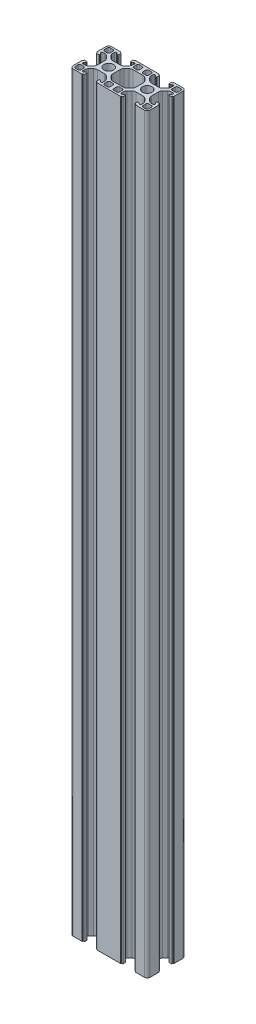
SolidWorks part; units mm, degrees
ref_plane "Спереди" through (0, 0, 0) normal (0, 0, 1) x (1, 0, 0)
ref_plane "Сверху" through (0, 0, 0) normal (0, 1, 0) x (1, 0, 0)
ref_plane "Справа" through (0, 0, 0) normal (1, 0, 0) x (0, 0, -1)
sketch "Эскиз1" plane through (0, 0, 0) normal (0, 1, 0) x (1, 0, 0)
  line L0 (-3.1522, 8.2837) -> (-1.6522, 6.7837) construction
  line L1 (18.3478, 9.7837) -> (15.3478, 6.7837) construction
  line L2 (-10.7522, 0.6837) -> (-0.7522, 10.6837) construction
  line L3 (9.2478, 4.6837) -> (11.1466, 4.6837)
  line L4 (9.2478, 0.6837) -> (19.2478, 10.6837) construction
  line L5 (16.8478, 8.2837) -> (15.3478, 9.7837) construction
  line L6 (12.5608, 5.2695) -> (13.862, 6.5707)
  line L7 (16.1478, 6.7837) -> (17.5478, 6.7837)
  line L8 (15.3478, 7.5837) -> (15.3478, 8.9837)
  line L9 (17.5478, 9.7837) -> (16.1478, 9.7837)
  line L10 (14.4478, 8.8837) -> (14.4478, 7.9849)
  line L11 (13.011, 8.757) -> (13.4914, 9.2373)
  line L12 (12.4478, 10.2328) -> (12.9478, 10.2328)
  line L13 (12.8343, 8.6837) -> (12.5478, 8.6837)
  line L14 (13.8449, 9.3837) -> (13.9478, 9.3837)
  line L15 (12.9478, 10.5337) -> (12.9478, 10.2328)
  line L16 (12.2978, 10.0828) -> (12.2978, 8.9337)
  line L17 (17.7478, 10.6837) -> (13.0978, 10.6837)
  line L18 (18.3478, 8.9837) -> (18.3478, 7.5837)
  line L19 (19.2478, 9.1837) -> (19.2478, 4.5337)
  line L20 (18.6469, 3.7337) -> (17.4978, 3.7337)
  line L21 (19.0978, 4.3837) -> (18.7969, 4.3837)
  line L22 (17.9478, 5.2808) -> (17.9478, 5.3837)
  line L23 (17.2478, 4.2702) -> (17.2478, 3.9837)
  line L24 (18.7969, 3.8837) -> (18.7969, 4.3837)
  line L25 (17.321, 4.447) -> (17.8014, 4.9273)
  line L26 (17.4478, 5.8837) -> (16.549, 5.8837)
  line L27 (13.8336, 3.9967) -> (15.1348, 5.2979)
  line L28 (13.2478, 0.6837) -> (13.2478, 2.5825)
  line L29 (13.2478, 0.6837) -> (13.2478, -1.2151)
  line L30 (13.8336, -2.6293) -> (15.1348, -3.9305)
  line L31 (15.3478, -6.2163) -> (15.3478, -7.6163)
  line L32 (16.1478, -5.4163) -> (17.5478, -5.4163)
  line L33 (18.3478, -7.6163) -> (18.3478, -6.2163)
  line L34 (17.4478, -4.5163) -> (16.549, -4.5163)
  line L35 (17.321, -3.0795) -> (17.8014, -3.5598)
  line L36 (18.7969, -2.5163) -> (18.7969, -3.0163)
  line L37 (17.2478, -2.9027) -> (17.2478, -2.6163)
  line L38 (17.9478, -3.9134) -> (17.9478, -4.0163)
  line L39 (19.0978, -3.0163) -> (18.7969, -3.0163)
  line L40 (18.6469, -2.3663) -> (17.4978, -2.3663)
  line L41 (19.2478, -7.8163) -> (19.2478, -3.1663)
  line L42 (17.5478, -8.4163) -> (16.1478, -8.4163)
  line L43 (17.7478, -9.3163) -> (13.0978, -9.3163)
  line L44 (12.2978, -8.7153) -> (12.2978, -7.5663)
  line L45 (12.9478, -9.1663) -> (12.9478, -8.8653)
  line L46 (13.8449, -8.0163) -> (13.9478, -8.0163)
  line L47 (12.8343, -7.3163) -> (12.5478, -7.3163)
  line L48 (12.4478, -8.8653) -> (12.9478, -8.8653)
  line L49 (13.011, -7.3895) -> (13.4914, -7.8698)
  line L50 (14.4478, -7.5163) -> (14.4478, -6.6175)
  line L51 (12.5608, -3.9021) -> (13.862, -5.2033)
  line L52 (9.2478, -3.3163) -> (11.1466, -3.3163)
  line L53 (18.3478, -8.4163) -> (15.3478, -5.4163) construction
  line L54 (9.2478, 0.6837) -> (19.2478, -9.3163) construction
  line L55 (16.8478, -6.9163) -> (18.3478, -5.4163) construction
  line L56 (9.2478, -3.3163) -> (7.349, -3.3163)
  line L57 (5.9348, -3.9021) -> (4.6336, -5.2033)
  line L58 (2.3478, -5.4163) -> (0.9478, -5.4163)
  line L59 (3.1478, -6.2163) -> (3.1478, -7.6163)
  line L60 (0.9478, -8.4163) -> (2.3478, -8.4163)
  line L61 (4.0478, -7.5163) -> (4.0478, -6.6175)
  line L62 (5.4846, -7.3895) -> (5.0043, -7.8698)
  line L63 (6.0478, -8.8653) -> (5.5478, -8.8653)
  line L64 (5.6614, -7.3163) -> (5.9478, -7.3163)
  line L65 (4.6507, -8.0163) -> (4.5478, -8.0163)
  line L66 (5.5478, -9.1663) -> (5.5478, -8.8653)
  line L67 (6.1978, -8.7153) -> (6.1978, -7.5663)
  line L68 (0.7478, -9.3163) -> (5.3978, -9.3163)
  line L69 (0.1478, -7.6163) -> (0.1478, -6.2163)
  line L70 (1.0478, -4.5163) -> (1.9466, -4.5163)
  line L71 (4.662, -2.6293) -> (3.3608, -3.9305)
  line L72 (5.2478, 0.6837) -> (5.2478, -1.2151)
  line L73 (-1.6522, 9.7837) -> (-4.6522, 6.7837) construction
  line L74 (0.1478, -8.4163) -> (3.1478, -5.4163) construction
  line L75 (-3.1522, -6.9163) -> (-4.6522, -8.4163) construction
  line L76 (9.2478, 0.6837) -> (-0.7522, -9.3163) construction
  line L77 (1.6478, -6.9163) -> (3.1478, -8.4163) construction
  line L78 (5.2478, 0.6837) -> (5.2478, 2.5825)
  line L79 (4.662, 3.9967) -> (3.3608, 5.2979)
  line L80 (3.1478, 7.5837) -> (3.1478, 8.9837)
  line L81 (2.3478, 6.7837) -> (0.9478, 6.7837)
  line L82 (0.1478, 8.9837) -> (0.1478, 7.5837)
  line L83 (1.0478, 5.8837) -> (1.9466, 5.8837)
  line L84 (0.9478, 9.7837) -> (2.3478, 9.7837)
  line L85 (0.7478, 10.6837) -> (5.3978, 10.6837)
  line L86 (6.1978, 10.0828) -> (6.1978, 8.9337)
  line L87 (5.5478, 10.5337) -> (5.5478, 10.2328)
  line L88 (4.6507, 9.3837) -> (4.5478, 9.3837)
  line L89 (5.6614, 8.6837) -> (5.9478, 8.6837)
  line L90 (6.0478, 10.2328) -> (5.5478, 10.2328)
  line L91 (5.4846, 8.757) -> (5.0043, 9.2373)
  line L92 (4.0478, 8.8837) -> (4.0478, 7.9849)
  line L93 (5.9348, 5.2695) -> (4.6336, 6.5707)
  line L94 (9.2478, 4.6837) -> (7.349, 4.6837)
  line L95 (-2.5162, 0.6837) -> (20.7522, 0.6837) construction
  line L96 (0.1478, 9.7837) -> (3.1478, 6.7837) construction
  line L97 (9.2478, -11.4027) -> (9.2478, 11.4027) construction
  line L98 (9.2478, 0.6837) -> (-0.7522, 10.6837) construction
  line L99 (1.6478, 8.2837) -> (0.1478, 6.7837) construction
  line L100 (-10.7522, 0.6837) -> (-0.7522, -9.3163) construction
  line L101 (-1.6522, -8.4163) -> (-4.6522, -5.4163) construction
  line L102 (-18.3522, -6.9163) -> (-19.8522, -5.4163) construction
  line L103 (-10.7522, 0.6837) -> (-20.7522, -9.3163) construction
  line L104 (-19.8522, -8.4163) -> (-16.8522, -5.4163) construction
  line L105 (-18.3522, 8.2837) -> (-16.8522, 9.7837) construction
  line L106 (-10.7522, 0.6837) -> (-20.7522, 10.6837) construction
  line L107 (-19.8522, 9.7837) -> (-16.8522, 6.7837) construction
  line L108 (-10.7522, 4.6837) -> (-8.8534, 4.6837)
  line L109 (-7.4392, 5.2695) -> (-6.138, 6.5707)
  line L110 (-5.5522, 8.8837) -> (-5.5522, 7.9849)
  line L111 (-6.989, 8.757) -> (-6.5086, 9.2373)
  line L112 (-7.5522, 10.2328) -> (-7.0522, 10.2328)
  line L113 (-7.1657, 8.6837) -> (-7.4522, 8.6837)
  line L114 (-6.1551, 9.3837) -> (-6.0522, 9.3837)
  line L115 (-7.0522, 10.5337) -> (-7.0522, 10.2328)
  line L116 (-7.7022, 10.0828) -> (-7.7022, 8.9337)
  line L117 (-2.2522, 10.6837) -> (-6.9022, 10.6837)
  line L118 (-2.4522, 9.7837) -> (-3.8522, 9.7837)
  line L119 (-2.5522, 5.8837) -> (-3.451, 5.8837)
  line L120 (-1.6522, 8.9837) -> (-1.6522, 7.5837)
  line L121 (-3.8522, 6.7837) -> (-2.4522, 6.7837)
  line L122 (-4.6522, 7.5837) -> (-4.6522, 8.9837)
  line L123 (-6.1664, 3.9967) -> (-4.8652, 5.2979)
  line L124 (-6.7522, 0.6837) -> (-6.7522, 2.5825)
  line L125 (-6.7522, 0.6837) -> (-6.7522, -1.2151)
  line L126 (-6.1664, -2.6293) -> (-4.8652, -3.9305)
  line L127 (-2.5522, -4.5163) -> (-3.451, -4.5163)
  line L128 (-1.6522, -7.6163) -> (-1.6522, -6.2163)
  line L129 (-2.2522, -9.3163) -> (-6.9022, -9.3163)
  line L130 (-7.7022, -8.7153) -> (-7.7022, -7.5663)
  line L131 (-7.0522, -9.1663) -> (-7.0522, -8.8653)
  line L132 (-6.1551, -8.0163) -> (-6.0522, -8.0163)
  line L133 (-7.1657, -7.3163) -> (-7.4522, -7.3163)
  line L134 (-7.5522, -8.8653) -> (-7.0522, -8.8653)
  line L135 (-6.989, -7.3895) -> (-6.5086, -7.8698)
  line L136 (-5.5522, -7.5163) -> (-5.5522, -6.6175)
  line L137 (-2.4522, -8.4163) -> (-3.8522, -8.4163)
  line L138 (-4.6522, -6.2163) -> (-4.6522, -7.6163)
  line L139 (-3.8522, -5.4163) -> (-2.4522, -5.4163)
  line L140 (-7.4392, -3.9021) -> (-6.138, -5.2033)
  line L141 (-10.7522, -3.3163) -> (-8.8534, -3.3163)
  line L142 (-10.7522, -3.3163) -> (-12.651, -3.3163)
  line L143 (-14.0652, -3.9021) -> (-15.3664, -5.2033)
  line L144 (-15.9522, -7.5163) -> (-15.9522, -6.6175)
  line L145 (-14.5154, -7.3895) -> (-14.9957, -7.8698)
  line L146 (-13.9522, -8.8653) -> (-14.4522, -8.8653)
  line L147 (-14.3386, -7.3163) -> (-14.0522, -7.3163)
  line L148 (-15.3493, -8.0163) -> (-15.4522, -8.0163)
  line L149 (-14.4522, -9.1663) -> (-14.4522, -8.8653)
  line L150 (-13.8022, -8.7153) -> (-13.8022, -7.5663)
  line L151 (-19.2522, -9.3163) -> (-14.6022, -9.3163)
  line L152 (-19.0522, -8.4163) -> (-17.6522, -8.4163)
  line L153 (-20.7522, -7.8163) -> (-20.7522, -3.1663)
  line L154 (-20.1512, -2.3663) -> (-19.0022, -2.3663)
  line L155 (-20.6022, -3.0163) -> (-20.3012, -3.0163)
  line L156 (-19.4522, -3.9134) -> (-19.4522, -4.0163)
  line L157 (-18.7522, -2.9027) -> (-18.7522, -2.6163)
  line L158 (-20.3012, -2.5163) -> (-20.3012, -3.0163)
  line L159 (-18.8254, -3.0795) -> (-19.3057, -3.5598)
  line L160 (-18.9522, -4.5163) -> (-18.0534, -4.5163)
  line L161 (-19.8522, -7.6163) -> (-19.8522, -6.2163)
  line L162 (-17.6522, -5.4163) -> (-19.0522, -5.4163)
  line L163 (-16.8522, -6.2163) -> (-16.8522, -7.6163)
  line L164 (-15.338, -2.6293) -> (-16.6392, -3.9305)
  line L165 (-14.7522, 0.6837) -> (-14.7522, -1.2151)
  line L166 (-14.7522, 0.6837) -> (-14.7522, 2.5825)
  line L167 (-15.338, 3.9967) -> (-16.6392, 5.2979)
  line L168 (-18.9522, 5.8837) -> (-18.0534, 5.8837)
  line L169 (-18.8254, 4.447) -> (-19.3057, 4.9273)
  line L170 (-20.3012, 3.8837) -> (-20.3012, 4.3837)
  line L171 (-18.7522, 4.2702) -> (-18.7522, 3.9837)
  line L172 (-19.4522, 5.2808) -> (-19.4522, 5.3837)
  line L173 (-20.6022, 4.3837) -> (-20.3012, 4.3837)
  line L174 (-20.1512, 3.7337) -> (-19.0022, 3.7337)
  line L175 (-20.7522, 9.1837) -> (-20.7522, 4.5337)
  line L176 (-19.8522, 8.9837) -> (-19.8522, 7.5837)
  line L177 (-19.2522, 10.6837) -> (-14.6022, 10.6837)
  line L178 (-13.8022, 10.0828) -> (-13.8022, 8.9337)
  line L179 (-14.4522, 10.5337) -> (-14.4522, 10.2328)
  line L180 (-15.3493, 9.3837) -> (-15.4522, 9.3837)
  line L181 (-14.3386, 8.6837) -> (-14.0522, 8.6837)
  line L182 (-13.9522, 10.2328) -> (-14.4522, 10.2328)
  line L183 (-14.5154, 8.757) -> (-14.9957, 9.2373)
  line L184 (-15.9522, 8.8837) -> (-15.9522, 7.9849)
  line L185 (-19.0522, 9.7837) -> (-17.6522, 9.7837)
  line L186 (-16.8522, 7.5837) -> (-16.8522, 8.9837)
  line L187 (-17.6522, 6.7837) -> (-19.0522, 6.7837)
  line L188 (-14.0652, 5.2695) -> (-15.3664, 6.5707)
  line L189 (-10.7522, 4.6837) -> (-12.651, 4.6837)
  line L190 (-2.2522, -9.3163) -> (0.7478, -9.3163)
  line L191 (-2.5522, -4.5163) -> (1.0478, -4.5163)
  line L192 (-2.5522, 5.8837) -> (1.0478, 5.8837)
  line L193 (-2.2522, 10.6837) -> (0.7478, 10.6837)
  arc A0 (18.3478, 8.9837) -> (17.5478, 9.7837) centre (17.5478, 8.9837) ccw
  arc A1 (16.1478, 9.7837) -> (15.3478, 8.9837) centre (16.1478, 8.9837) ccw
  arc A2 (16.1478, 6.7837) -> (15.3478, 7.5837) centre (16.1478, 7.5837) cw
  arc A3 (17.7478, 10.6837) -> (19.2478, 9.1837) centre (17.7478, 9.1837) cw
  arc A4 (12.4478, 10.2328) -> (12.2978, 10.0828) centre (12.4478, 10.0828) ccw
  arc A5 (13.0978, 10.6837) -> (12.9478, 10.5337) centre (13.0978, 10.5337) ccw
  arc A6 (12.8343, 8.6837) -> (13.011, 8.757) centre (12.8343, 8.9337) ccw
  arc A7 (12.5478, 8.6837) -> (12.2978, 8.9337) centre (12.5478, 8.9337) cw
  arc A8 (13.4914, 9.2373) -> (13.8449, 9.3837) centre (13.8449, 8.8837) cw
  arc A9 (13.9478, 9.3837) -> (14.4478, 8.8837) centre (13.9478, 8.8837) cw
  arc A10 (11.7478, 0.6837) -> (9.2478, 3.1837) centre (9.2478, 0.6837) ccw
  arc A11 (11.1466, 4.6837) -> (12.5608, 5.2695) centre (11.1466, 6.6837) ccw
  arc A12 (14.4478, 7.9849) -> (13.862, 6.5707) centre (12.4478, 7.9849) cw
  arc A13 (18.3478, 7.5837) -> (17.5478, 6.7837) centre (17.5478, 7.5837) cw
  arc A14 (17.9478, 5.3837) -> (17.4478, 5.8837) centre (17.4478, 5.3837) ccw
  arc A15 (17.8014, 4.9273) -> (17.9478, 5.2808) centre (17.4478, 5.2808) ccw
  arc A16 (17.2478, 3.9837) -> (17.4978, 3.7337) centre (17.4978, 3.9837) ccw
  arc A17 (17.2478, 4.2702) -> (17.321, 4.447) centre (17.4978, 4.2702) cw
  arc A18 (19.2478, 4.5337) -> (19.0978, 4.3837) centre (19.0978, 4.5337) cw
  arc A19 (18.7969, 3.8837) -> (18.6469, 3.7337) centre (18.6469, 3.8837) cw
  arc A20 (16.549, 5.8837) -> (15.1348, 5.2979) centre (16.549, 3.8837) ccw
  arc A21 (13.2478, 2.5825) -> (13.8336, 3.9967) centre (15.2478, 2.5825) cw
  arc A22 (17.5478, -8.4163) -> (18.3478, -7.6163) centre (17.5478, -7.6163) ccw
  arc A23 (18.3478, -6.2163) -> (17.5478, -5.4163) centre (17.5478, -6.2163) ccw
  arc A24 (15.3478, -6.2163) -> (16.1478, -5.4163) centre (16.1478, -6.2163) cw
  arc A25 (19.2478, -7.8163) -> (17.7478, -9.3163) centre (17.7478, -7.8163) cw
  arc A26 (18.7969, -2.5163) -> (18.6469, -2.3663) centre (18.6469, -2.5163) ccw
  arc A27 (19.2478, -3.1663) -> (19.0978, -3.0163) centre (19.0978, -3.1663) ccw
  arc A28 (17.2478, -2.9027) -> (17.321, -3.0795) centre (17.4978, -2.9027) ccw
  arc A29 (17.2478, -2.6163) -> (17.4978, -2.3663) centre (17.4978, -2.6163) cw
  arc A30 (17.8014, -3.5598) -> (17.9478, -3.9134) centre (17.4478, -3.9134) cw
  arc A31 (17.9478, -4.0163) -> (17.4478, -4.5163) centre (17.4478, -4.0163) cw
  arc A32 (9.2478, -1.8163) -> (11.7478, 0.6837) centre (9.2478, 0.6837) ccw
  arc A33 (13.2478, -1.2151) -> (13.8336, -2.6293) centre (15.2478, -1.2151) ccw
  arc A34 (16.549, -4.5163) -> (15.1348, -3.9305) centre (16.549, -2.5163) cw
  arc A35 (16.1478, -8.4163) -> (15.3478, -7.6163) centre (16.1478, -7.6163) cw
  arc A36 (13.9478, -8.0163) -> (14.4478, -7.5163) centre (13.9478, -7.5163) ccw
  arc A37 (13.4914, -7.8698) -> (13.8449, -8.0163) centre (13.8449, -7.5163) ccw
  arc A38 (12.5478, -7.3163) -> (12.2978, -7.5663) centre (12.5478, -7.5663) ccw
  arc A39 (12.8343, -7.3163) -> (13.011, -7.3895) centre (12.8343, -7.5663) cw
  arc A40 (13.0978, -9.3163) -> (12.9478, -9.1663) centre (13.0978, -9.1663) cw
  arc A41 (12.4478, -8.8653) -> (12.2978, -8.7153) centre (12.4478, -8.7153) cw
  arc A42 (14.4478, -6.6175) -> (13.862, -5.2033) centre (12.4478, -6.6175) ccw
  arc A43 (11.1466, -3.3163) -> (12.5608, -3.9021) centre (11.1466, -5.3163) cw
  arc A44 (0.1478, -7.6163) -> (0.9478, -8.4163) centre (0.9478, -7.6163) ccw
  arc A45 (2.3478, -8.4163) -> (3.1478, -7.6163) centre (2.3478, -7.6163) ccw
  arc A46 (2.3478, -5.4163) -> (3.1478, -6.2163) centre (2.3478, -6.2163) cw
  arc A47 (6.0478, -8.8653) -> (6.1978, -8.7153) centre (6.0478, -8.7153) ccw
  arc A48 (5.3978, -9.3163) -> (5.5478, -9.1663) centre (5.3978, -9.1663) ccw
  arc A49 (5.6614, -7.3163) -> (5.4846, -7.3895) centre (5.6614, -7.5663) ccw
  arc A50 (5.9478, -7.3163) -> (6.1978, -7.5663) centre (5.9478, -7.5663) cw
  arc A51 (5.0043, -7.8698) -> (4.6507, -8.0163) centre (4.6507, -7.5163) cw
  arc A52 (4.5478, -8.0163) -> (4.0478, -7.5163) centre (4.5478, -7.5163) cw
  arc A53 (6.7478, 0.6837) -> (9.2478, -1.8163) centre (9.2478, 0.6837) ccw
  arc A54 (7.349, -3.3163) -> (5.9348, -3.9021) centre (7.349, -5.3163) ccw
  arc A55 (4.0478, -6.6175) -> (4.6336, -5.2033) centre (6.0478, -6.6175) cw
  arc A56 (0.1478, -6.2163) -> (0.9478, -5.4163) centre (0.9478, -6.2163) cw
  arc A57 (1.9466, -4.5163) -> (3.3608, -3.9305) centre (1.9466, -2.5163) ccw
  arc A58 (5.2478, -1.2151) -> (4.662, -2.6293) centre (3.2478, -1.2151) cw
  arc A59 (0.9478, 9.7837) -> (0.1478, 8.9837) centre (0.9478, 8.9837) ccw
  arc A60 (0.1478, 7.5837) -> (0.9478, 6.7837) centre (0.9478, 7.5837) ccw
  arc A61 (3.1478, 7.5837) -> (2.3478, 6.7837) centre (2.3478, 7.5837) cw
  arc A62 (9.2478, 3.1837) -> (6.7478, 0.6837) centre (9.2478, 0.6837) ccw
  arc A63 (5.2478, 2.5825) -> (4.662, 3.9967) centre (3.2478, 2.5825) ccw
  arc A64 (1.9466, 5.8837) -> (3.3608, 5.2979) centre (1.9466, 3.8837) cw
  arc A65 (2.3478, 9.7837) -> (3.1478, 8.9837) centre (2.3478, 8.9837) cw
  arc A66 (4.5478, 9.3837) -> (4.0478, 8.8837) centre (4.5478, 8.8837) ccw
  arc A67 (5.0043, 9.2373) -> (4.6507, 9.3837) centre (4.6507, 8.8837) ccw
  arc A68 (5.9478, 8.6837) -> (6.1978, 8.9337) centre (5.9478, 8.9337) ccw
  arc A69 (5.6614, 8.6837) -> (5.4846, 8.757) centre (5.6614, 8.9337) cw
  arc A70 (5.3978, 10.6837) -> (5.5478, 10.5337) centre (5.3978, 10.5337) cw
  arc A71 (6.0478, 10.2328) -> (6.1978, 10.0828) centre (6.0478, 10.0828) cw
  arc A72 (4.0478, 7.9849) -> (4.6336, 6.5707) centre (6.0478, 7.9849) ccw
  arc A73 (7.349, 4.6837) -> (5.9348, 5.2695) centre (7.349, 6.6837) cw
  arc A74 (-8.8534, 4.6837) -> (-7.4392, 5.2695) centre (-8.8534, 6.6837) ccw
  arc A75 (-5.5522, 7.9849) -> (-6.138, 6.5707) centre (-7.5522, 7.9849) cw
  arc A76 (-7.5522, 10.2328) -> (-7.7022, 10.0828) centre (-7.5522, 10.0828) ccw
  arc A77 (-6.9022, 10.6837) -> (-7.0522, 10.5337) centre (-6.9022, 10.5337) ccw
  arc A78 (-7.1657, 8.6837) -> (-6.989, 8.757) centre (-7.1657, 8.9337) ccw
  arc A79 (-7.4522, 8.6837) -> (-7.7022, 8.9337) centre (-7.4522, 8.9337) cw
  arc A80 (-6.5086, 9.2373) -> (-6.1551, 9.3837) centre (-6.1551, 8.8837) cw
  arc A81 (-6.0522, 9.3837) -> (-5.5522, 8.8837) centre (-6.0522, 8.8837) cw
  arc A82 (-3.8522, 9.7837) -> (-4.6522, 8.9837) centre (-3.8522, 8.9837) ccw
  arc A83 (-3.451, 5.8837) -> (-4.8652, 5.2979) centre (-3.451, 3.8837) ccw
  arc A84 (-6.7522, 2.5825) -> (-6.1664, 3.9967) centre (-4.7522, 2.5825) cw
  arc A85 (-10.7522, 3.1837) -> (-8.2522, 0.6837) centre (-10.7522, 0.6837) cw
  arc A86 (-4.6522, 7.5837) -> (-3.8522, 6.7837) centre (-3.8522, 7.5837) ccw
  arc A87 (-1.6522, 7.5837) -> (-2.4522, 6.7837) centre (-2.4522, 7.5837) cw
  arc A88 (-2.4522, 9.7837) -> (-1.6522, 8.9837) centre (-2.4522, 8.9837) cw
  arc A89 (-6.7522, -1.2151) -> (-6.1664, -2.6293) centre (-4.7522, -1.2151) ccw
  arc A90 (-3.451, -4.5163) -> (-4.8652, -3.9305) centre (-3.451, -2.5163) cw
  arc A91 (-1.6522, -6.2163) -> (-2.4522, -5.4163) centre (-2.4522, -6.2163) ccw
  arc A92 (-5.5522, -6.6175) -> (-6.138, -5.2033) centre (-7.5522, -6.6175) ccw
  arc A93 (-8.8534, -3.3163) -> (-7.4392, -3.9021) centre (-8.8534, -5.3163) cw
  arc A94 (-8.2522, 0.6837) -> (-10.7522, -1.8163) centre (-10.7522, 0.6837) cw
  arc A95 (-6.0522, -8.0163) -> (-5.5522, -7.5163) centre (-6.0522, -7.5163) ccw
  arc A96 (-6.5086, -7.8698) -> (-6.1551, -8.0163) centre (-6.1551, -7.5163) ccw
  arc A97 (-7.4522, -7.3163) -> (-7.7022, -7.5663) centre (-7.4522, -7.5663) ccw
  arc A98 (-7.1657, -7.3163) -> (-6.989, -7.3895) centre (-7.1657, -7.5663) cw
  arc A99 (-6.9022, -9.3163) -> (-7.0522, -9.1663) centre (-6.9022, -9.1663) cw
  arc A100 (-7.5522, -8.8653) -> (-7.7022, -8.7153) centre (-7.5522, -8.7153) cw
  arc A101 (-3.8522, -5.4163) -> (-4.6522, -6.2163) centre (-3.8522, -6.2163) ccw
  arc A102 (-3.8522, -8.4163) -> (-4.6522, -7.6163) centre (-3.8522, -7.6163) cw
  arc A103 (-1.6522, -7.6163) -> (-2.4522, -8.4163) centre (-2.4522, -7.6163) cw
  arc A104 (-12.651, -3.3163) -> (-14.0652, -3.9021) centre (-12.651, -5.3163) ccw
  arc A105 (-15.9522, -6.6175) -> (-15.3664, -5.2033) centre (-13.9522, -6.6175) cw
  arc A106 (-13.9522, -8.8653) -> (-13.8022, -8.7153) centre (-13.9522, -8.7153) ccw
  arc A107 (-14.6022, -9.3163) -> (-14.4522, -9.1663) centre (-14.6022, -9.1663) ccw
  arc A108 (-14.3386, -7.3163) -> (-14.5154, -7.3895) centre (-14.3386, -7.5663) ccw
  arc A109 (-14.0522, -7.3163) -> (-13.8022, -7.5663) centre (-14.0522, -7.5663) cw
  arc A110 (-14.9957, -7.8698) -> (-15.3493, -8.0163) centre (-15.3493, -7.5163) cw
  arc A111 (-15.4522, -8.0163) -> (-15.9522, -7.5163) centre (-15.4522, -7.5163) cw
  arc A112 (-17.6522, -8.4163) -> (-16.8522, -7.6163) centre (-17.6522, -7.6163) ccw
  arc A113 (-18.0534, -4.5163) -> (-16.6392, -3.9305) centre (-18.0534, -2.5163) ccw
  arc A114 (-14.7522, -1.2151) -> (-15.338, -2.6293) centre (-16.7522, -1.2151) cw
  arc A115 (-10.7522, -1.8163) -> (-13.2522, 0.6837) centre (-10.7522, 0.6837) cw
  arc A116 (-19.4522, -4.0163) -> (-18.9522, -4.5163) centre (-18.9522, -4.0163) ccw
  arc A117 (-19.3057, -3.5598) -> (-19.4522, -3.9134) centre (-18.9522, -3.9134) ccw
  arc A118 (-18.7522, -2.6163) -> (-19.0022, -2.3663) centre (-19.0022, -2.6163) ccw
  arc A119 (-18.7522, -2.9027) -> (-18.8254, -3.0795) centre (-19.0022, -2.9027) cw
  arc A120 (-20.7522, -3.1663) -> (-20.6022, -3.0163) centre (-20.6022, -3.1663) cw
  arc A121 (-20.3012, -2.5163) -> (-20.1512, -2.3663) centre (-20.1512, -2.5163) cw
  arc A122 (-20.7522, -7.8163) -> (-19.2522, -9.3163) centre (-19.2522, -7.8163) ccw
  arc A123 (-16.8522, -6.2163) -> (-17.6522, -5.4163) centre (-17.6522, -6.2163) ccw
  arc A124 (-19.8522, -6.2163) -> (-19.0522, -5.4163) centre (-19.0522, -6.2163) cw
  arc A125 (-19.0522, -8.4163) -> (-19.8522, -7.6163) centre (-19.0522, -7.6163) cw
  arc A126 (-14.7522, 2.5825) -> (-15.338, 3.9967) centre (-16.7522, 2.5825) ccw
  arc A127 (-18.0534, 5.8837) -> (-16.6392, 5.2979) centre (-18.0534, 3.8837) cw
  arc A128 (-20.3012, 3.8837) -> (-20.1512, 3.7337) centre (-20.1512, 3.8837) ccw
  arc A129 (-20.7522, 4.5337) -> (-20.6022, 4.3837) centre (-20.6022, 4.5337) ccw
  arc A130 (-18.7522, 4.2702) -> (-18.8254, 4.447) centre (-19.0022, 4.2702) ccw
  arc A131 (-18.7522, 3.9837) -> (-19.0022, 3.7337) centre (-19.0022, 3.9837) cw
  arc A132 (-19.3057, 4.9273) -> (-19.4522, 5.2808) centre (-18.9522, 5.2808) cw
  arc A133 (-19.4522, 5.3837) -> (-18.9522, 5.8837) centre (-18.9522, 5.3837) cw
  arc A134 (-19.8522, 7.5837) -> (-19.0522, 6.7837) centre (-19.0522, 7.5837) ccw
  arc A135 (-15.9522, 7.9849) -> (-15.3664, 6.5707) centre (-13.9522, 7.9849) ccw
  arc A136 (-12.651, 4.6837) -> (-14.0652, 5.2695) centre (-12.651, 6.6837) cw
  arc A137 (-13.2522, 0.6837) -> (-10.7522, 3.1837) centre (-10.7522, 0.6837) cw
  arc A138 (-15.4522, 9.3837) -> (-15.9522, 8.8837) centre (-15.4522, 8.8837) ccw
  arc A139 (-14.9957, 9.2373) -> (-15.3493, 9.3837) centre (-15.3493, 8.8837) ccw
  arc A140 (-14.0522, 8.6837) -> (-13.8022, 8.9337) centre (-14.0522, 8.9337) ccw
  arc A141 (-14.3386, 8.6837) -> (-14.5154, 8.757) centre (-14.3386, 8.9337) cw
  arc A142 (-14.6022, 10.6837) -> (-14.4522, 10.5337) centre (-14.6022, 10.5337) cw
  arc A143 (-13.9522, 10.2328) -> (-13.8022, 10.0828) centre (-13.9522, 10.0828) cw
  arc A144 (-19.2522, 10.6837) -> (-20.7522, 9.1837) centre (-19.2522, 9.1837) ccw
  arc A145 (-17.6522, 6.7837) -> (-16.8522, 7.5837) centre (-17.6522, 7.5837) ccw
  arc A146 (-17.6522, 9.7837) -> (-16.8522, 8.9837) centre (-17.6522, 8.9837) cw
  arc A147 (-19.8522, 8.9837) -> (-19.0522, 9.7837) centre (-19.0522, 8.9837) cw
  point P0 (9.2478, 0.6837)
  point P12 (9.2478, 0.6837)
  point P45 (17.9478, 4.3837)
  point P104 (12.9478, -8.0163)
  point P155 (12.9478, 9.3837)
  point P163 (17.9478, -3.0163)
  point P164 (9.2478, -3.2405)
  point P166 (9.2478, 0.6837)
  point P224 (5.5478, -8.0163)
  point P225 (5.3236, 0.6837)
  point P227 (9.2478, 0.6837)
  point P267 (5.5478, 9.3837)
  point P272 (13.1721, 0.6837)
  point P288 (9.2478, 4.608)
  point P290 (9.2478, 0.6837)
  point P515 (-10.7522, 4.608)
  point P516 (-14.6764, 0.6837)
  point P517 (-7.0522, 9.3837)
  point P518 (-6.8279, 0.6837)
  point P519 (-7.0522, -8.0163)
  point P520 (-10.7522, -3.2405)
  point P521 (-19.4522, -3.0163)
  point P522 (-14.4522, 9.3837)
  point P523 (-14.4522, -8.0163)
  point P524 (-19.4522, 4.3837)
extrude "Бобышка-Вытянуть1" add sketch "Эскиз1" along normal blind 390
